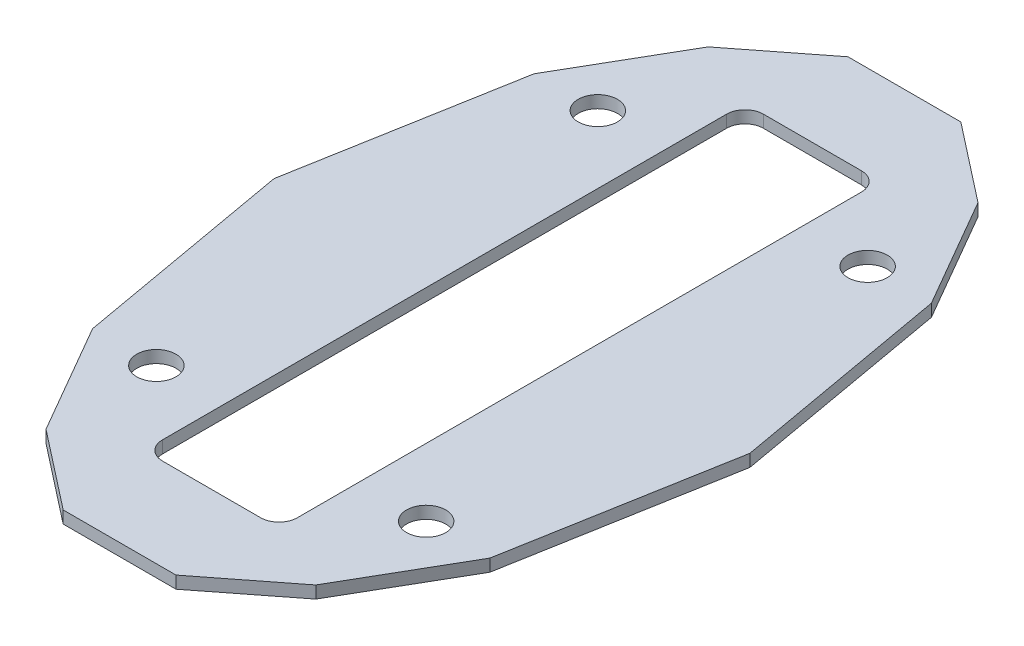
SolidWorks part; units mm, degrees
ref_plane "Front" through (0, 0, 0) normal (0, 0, 1) x (1, 0, 0)
ref_plane "Top" through (0, 0, 0) normal (0, 1, 0) x (1, 0, 0)
ref_plane "Right" through (0, 0, 0) normal (1, 0, 0) x (0, 0, -1)
sketch "Sketch1" plane through (0, 0, 0) normal (0, 1, 0) x (1, 0, 0)
  line L0 (0, 77.2463) -> (0, -71.4758) construction
  line L1 (-72.6561, 0) -> (58.4921, 0) construction
  line L2 (-59.5413, 18) -> (53.7708, 18) construction
  line L3 (61.1151, 27) -> (-45.6396, 27) construction
  line L4 (4.6, 88.2628) -> (4.6, -14.0329) construction
  line L5 (11, 88.2628) -> (11, -14.0329) construction
  line L6 (16.2, 88.2628) -> (16.2, -14.0329) construction
  line L7 (19.4, 88.2628) -> (19.4, -14.0329) construction
  line L8 (-59.5413, 32) -> (61.1151, 32) construction
  line L9 (19.4, 0) -> (16.2, 18)
  line L10 (16.2, 18) -> (11, 27)
  line L11 (11, 27) -> (4.6, 32)
  line L12 (4.6, 32) -> (-4.6, 32)
  line L13 (-19.4, 0) -> (-16.2, 18)
  line L14 (-16.2, 18) -> (-11, 27)
  line L15 (-11, 27) -> (-4.6, 32)
  line L16 (19.4, 0) -> (16.2, -18)
  line L17 (16.2, -18) -> (11, -27)
  line L18 (11, -27) -> (4.6, -32)
  line L19 (4.6, -32) -> (-4.6, -32)
  line L20 (-11, -27) -> (-4.6, -32)
  line L21 (-16.2, -18) -> (-11, -27)
  line L22 (-19.4, 0) -> (-16.2, -18)
  point P28 (0, 32)
  dimension "D1" = 18
  dimension "D2" = 27
  dimension "D3" = 32
  dimension "D4" = 4.6
  dimension "D5" = 11
  dimension "D6" = 16.2
  dimension "D7" = 19.4
extrude "Boss-Extrude1" add sketch "Sketch1" along normal blind 1
sketch "Sketch2" plane through (0, 1, 0) normal (0, 1, 0) x (1, 0, 0)
  line L1 (-5.5, -24.5) -> (5.5, -24.5)
  line L2 (-5.5, -24.5) -> (-5.5, 24.5)
  line L3 (-5.5, 24.5) -> (5.5, 24.5)
  line L4 (5.5, -24.5) -> (5.5, 24.5)
  line L5 (-5.5, -24.5) -> (5.5, 24.5) construction
  line L6 (-5.5, 24.5) -> (5.5, -24.5) construction
  point P0 (0, 0)
  dimension "D1" = 11
  dimension "D2" = 49
extrude "Cut-Extrude1" cut sketch "Sketch2" against normal through all
fillet "Fillet1" radius 1.5 4 edges at (5.5, 0.5, 24.5) (-5.5, 0.5, 24.5) (-5.5, 0.5, -24.5) (5.5, 0.5, -24.5)
sketch "Sketch3" plane through (0, 1, 0) normal (0, 1, 0) x (1, 0, 0)
  line L0 (-11, -35.5506) -> (-11, 34.4275) construction
  line L1 (-41.0366, 18) -> (26.3498, 18) construction
  line L2 (0, 12.3974) -> (0, -7.473) construction
  line L3 (-4.406, 0) -> (3.7149, 0) construction
  circle A0 centre (-11, 18) radius 1.6
  circle A1 centre (11, 18) radius 1.6
  circle A2 centre (-11, -18) radius 1.6
  circle A3 centre (11, -18) radius 1.6
  dimension "D3" = 3.2
  dimension "D1" = 11
  dimension "D2" = 18
extrude "Cut-Extrude2" cut sketch "Sketch3" against normal through all
